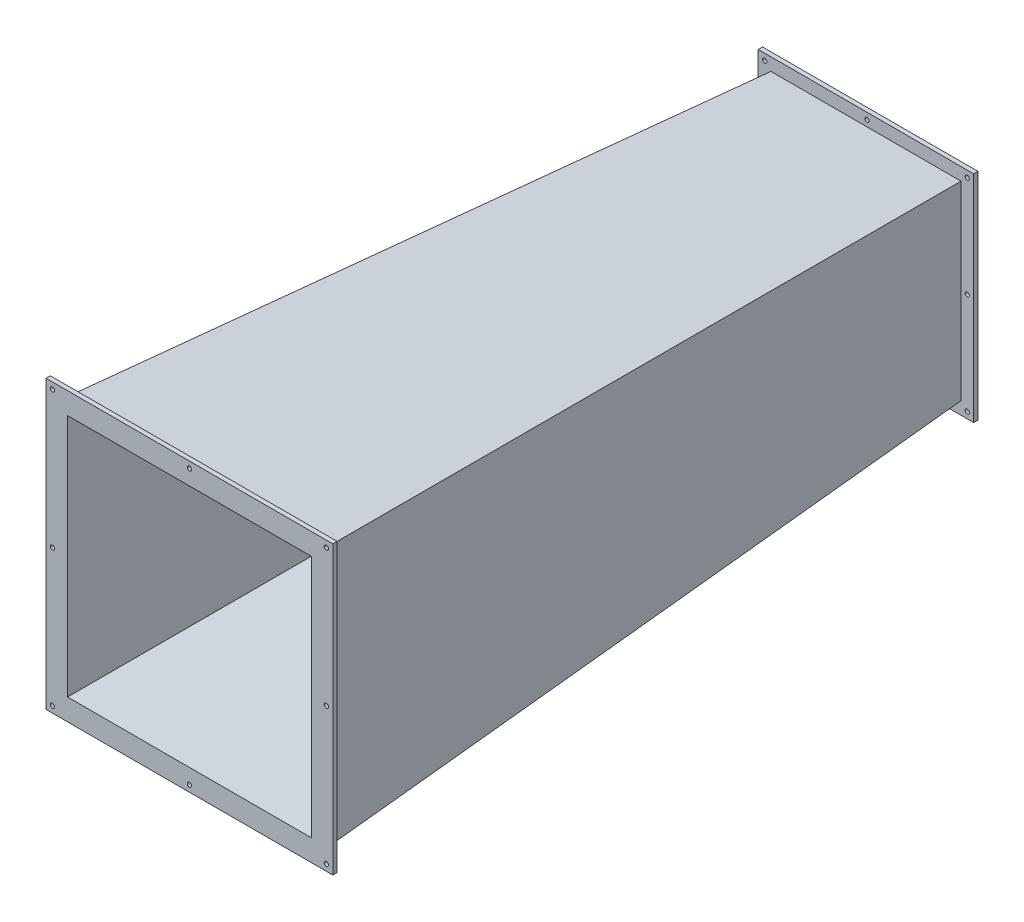
SolidWorks part; units mm, degrees
ref_plane "Front Plane" through (0, 0, 0) normal (0, 0, 1) x (1, 0, 0)
ref_plane "Top Plane" through (0, 0, 0) normal (0, 1, 0) x (1, 0, 0)
ref_plane "Right Plane" through (0, 0, 0) normal (1, 0, 0) x (0, 0, -1)
sketch "Sketch1" plane through (0, 0, 0) normal (0, 0, 1) x (1, 0, 0)
  line L0 (0, 100) -> (0, -100) construction
  line L1 (-100, -100) -> (100, -100)
  line L2 (-100, -100) -> (-100, 100)
  line L3 (-100, 100) -> (100, 100)
  line L4 (100, -100) -> (100, 100)
  line L5 (-100, -100) -> (100, 100) construction
  line L6 (-100, 100) -> (100, -100) construction
  line L7 (-110, 110) -> (110, 110)
  line L8 (110, -110) -> (110, 110)
  line L9 (-110, -110) -> (110, -110)
  line L10 (-110, -110) -> (-110, 110)
  point P0 (0, 0)
  dimension "D1" = 10
ref_plane "Plane1" through (0, 0, 790) normal (0, 0, 1) x (1, 0, 0)
sketch "Sketch3" plane through (0, 0, 790) normal (0, 0, 1) x (1, 0, 0)
  line L0 (151.4214, 151.4214) -> (-151.4214, 151.4214)
  line L1 (141.4213, -141.4213) -> (-141.4213, -141.4214)
  line L2 (141.4213, -141.4213) -> (141.4213, 141.4213)
  line L3 (141.4213, 141.4213) -> (-141.4213, 141.4213)
  line L4 (-141.4213, -141.4214) -> (-141.4213, 141.4213)
  line L5 (141.4213, -141.4213) -> (-141.4213, 141.4213) construction
  line L6 (141.4213, 141.4213) -> (-141.4213, -141.4214) construction
  line L7 (-151.4214, -151.4214) -> (-151.4214, 151.4214)
  line L8 (151.4214, -151.4214) -> (-151.4214, -151.4214)
  line L9 (151.4214, -151.4214) -> (151.4214, 151.4214)
  point P0 (0, 0)
  dimension "D1" = 10
ref_plane "Plane2" through (0, 0, 0) normal (-1, 0, 0) x (0, -1, 0)
extrude "Boss-Extrude1" add sketch "Sketch3" against normal blind 790 draft 3 contours L4 L1 L2 L3 | L8 L9 L0 L7 L1 L4 L3 L2
sketch "Sketch6" plane through (0, 0, 0) normal (0, 0, -1) x (-1, 0, 0)
  line L1 (-100, -100) -> (100, -100)
  line L2 (-100, -100) -> (-100, 100)
  line L3 (-100, 100) -> (100, 100)
  line L4 (100, -100) -> (100, 100)
  line L5 (-100, -100) -> (100, 100) construction
  line L6 (-100, 100) -> (100, -100) construction
  point P0 (0, 0)
extrude "Cut-Extrude3" cut sketch "Sketch6" against normal blind 790 draft 3 draft outward yes
sketch "Sketch7" plane through (0, 0, 0) normal (0, 0, -1) x (-1, 0, 0)
  line L1 (100, -100) -> (-100, -100)
  line L2 (100, -100) -> (100, 100)
  line L3 (100, 100) -> (-100, 100)
  line L4 (-100, -100) -> (-100, 100)
  line L5 (100, -100) -> (-100, 100) construction
  line L6 (100, 100) -> (-100, -100) construction
  line L7 (125, 125) -> (-125, 125)
  line L8 (-125, -125) -> (-125, 125)
  line L9 (125, -125) -> (-125, -125)
  line L10 (125, -125) -> (125, 125)
  line L11 (-110.0192, 110.0192) -> (-125, 125) construction
  line L12 (0, -110) -> (0, -125) construction
  line L13 (110, -110) -> (-110, -110) construction
  circle A0 centre (0, -117.5) radius 2.5
  circle A1 centre (-117.5096, 117.5096) radius 2.5
  circle A2 centre (117.5096, -117.5096) radius 2.5
  circle A3 centre (-117.5, 0) radius 2.5
  circle A4 centre (-117.5096, -117.5096) radius 2.5
  circle A5 centre (117.5096, 117.5096) radius 2.5
  circle A6 centre (117.5, 0) radius 2.5
  circle A7 centre (-1.218, 117.5096) radius 2.5
  dimension "D1" = 25
extrude "Boss-Extrude2" add sketch "Sketch7" against normal blind 5
sketch "Sketch8" plane through (0, 0, 790) normal (0, 0, 1) x (1, 0, 0)
  line L0 (166.4021, 166.4021) -> (-166.4021, 166.4021)
  line L1 (141.4021, -141.4021) -> (-141.4021, -141.4021)
  line L2 (141.4021, -141.4021) -> (141.4021, 141.4021)
  line L3 (141.4021, 141.4021) -> (-141.4021, 141.4021)
  line L4 (-141.4021, -141.4021) -> (-141.4021, 141.4021)
  line L5 (141.4021, -141.4021) -> (-141.4021, 141.4021) construction
  line L6 (141.4021, 141.4021) -> (-141.4021, -141.4021) construction
  line L7 (-166.4021, -166.4021) -> (-166.4021, 166.4021)
  line L8 (166.4021, -166.4021) -> (-166.4021, -166.4021)
  line L9 (166.4021, -166.4021) -> (166.4021, 166.4021)
  line L10 (-151.4214, 151.4214) -> (-166.4021, 166.4021) construction
  line L11 (-166.4021, 0) -> (-151.4214, 0) construction
  line L12 (-151.4214, -151.4214) -> (-151.4214, 151.4214) construction
  circle A0 centre (-158.9117, 0) radius 2.5
  circle A1 centre (-158.9117, 158.9117) radius 2.5
  circle A2 centre (158.9117, -158.9117) radius 2.5
  circle A3 centre (0, -158.9117) radius 2.5
  circle A4 centre (158.9117, 158.9117) radius 2.5
  circle A5 centre (0, 158.9117) radius 2.5
  circle A6 centre (-158.9117, -158.9117) radius 2.5
  circle A7 centre (158.9117, 0) radius 2.5
  point P0 (0, 0)
  dimension "D1" = 25
extrude "Boss-Extrude3" add sketch "Sketch8" against normal blind 5
